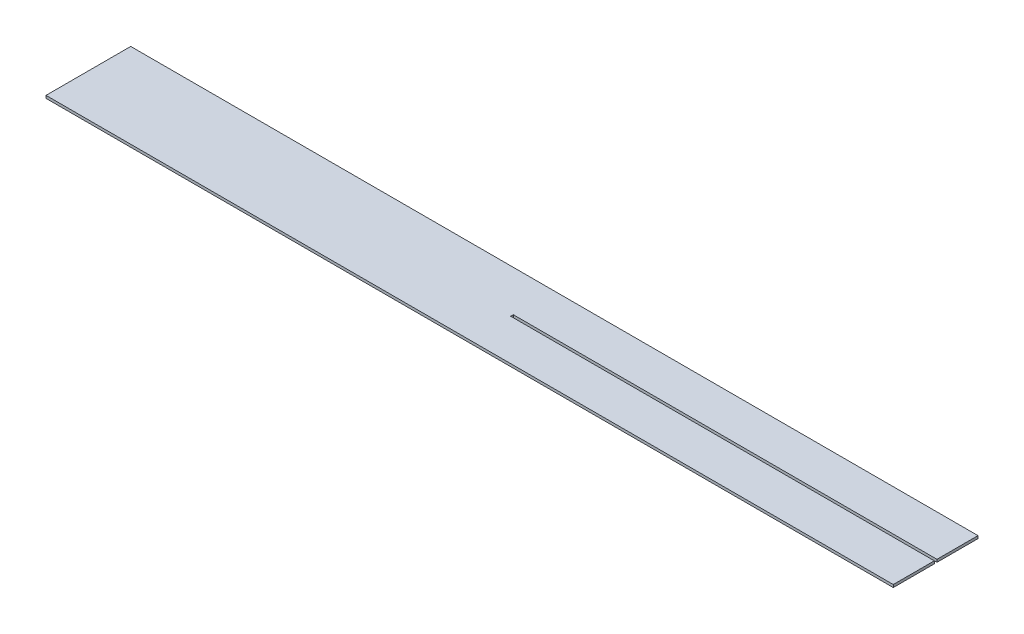
SolidWorks part; units mm, degrees
ref_plane "Front" through (0, 0, 0) normal (0, 0, 1) x (1, 0, 0)
ref_plane "Top" through (0, 0, 0) normal (0, 1, 0) x (1, 0, 0)
ref_plane "Right" through (0, 0, 0) normal (1, 0, 0) x (0, 0, -1)
sketch "Sketch1" plane through (0, 0, 0) normal (0, 1, 0) x (1, 0, 0)
  line L1 (-254, -25.4) -> (254, -25.4)
  line L2 (-254, -25.4) -> (-254, 25.4)
  line L3 (-254, 25.4) -> (254, 25.4)
  line L4 (254, -25.4) -> (254, 25.4)
  line L5 (0, 25.4) -> (0, -25.4) construction
  line L6 (-254, 0) -> (254, 0) construction
  line L7 (508, -0.7938) -> (0, -0.7938)
  line L8 (508, -0.7938) -> (508, 0.7937)
  line L9 (508, 0.7937) -> (0, 0.7937)
  line L10 (0, -0.7938) -> (0, 0.7937)
  line L11 (254, 0.7937) -> (254, -0.7938) construction
  line L12 (508, 0) -> (0, 0) construction
  point P0 (0, 0)
  dimension "D1" = 508
  dimension "D2" = 50.8
  dimension "D3" = 1.5875
extrude "Boss-Extrude1" add sketch "Sketch1" along normal blind 1.5875 contours L7 L10 L9 L4 L3 L2 L1
